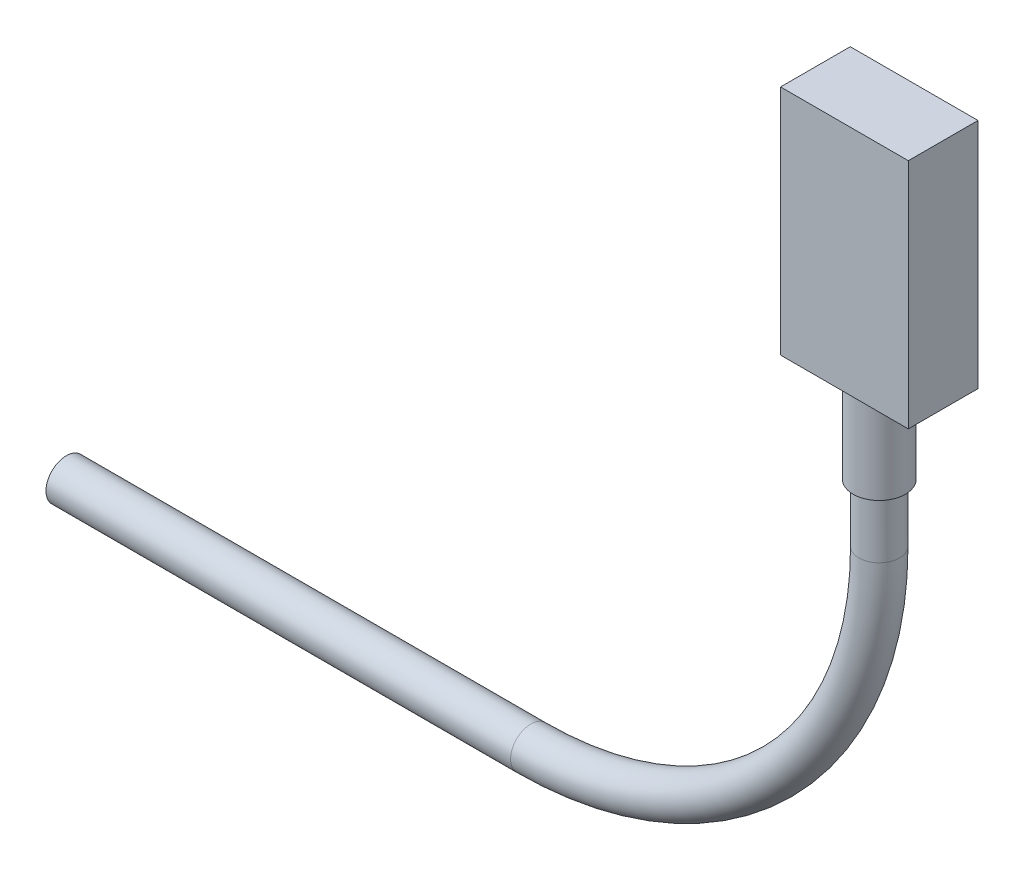
SolidWorks part; units mm, degrees
ref_plane "Front Plane" through (0, 0, 0) normal (0, 0, 1) x (1, 0, 0)
ref_plane "Top Plane" through (0, 0, 0) normal (0, 1, 0) x (1, 0, 0)
ref_plane "Right Plane" through (0, 0, 0) normal (1, 0, 0) x (0, 0, -1)
sketch "Sketch1" plane through (0, 0, 0) normal (0, 1, 0) x (1, 0, 0)
  line L1 (-5.5, 3) -> (5.5, 3)
  line L2 (-5.5, 3) -> (-5.5, -3)
  line L3 (-5.5, -3) -> (5.5, -3)
  line L4 (5.5, 3) -> (5.5, -3)
extrude "Overmould" add sketch "Sketch1" against normal blind 20
ref_plane "Plane_ym20" through (0, -20, 0) normal (0, 1, 0) x (1, 0, 0)
sketch "Sketch2" plane through (0, -20, 0) normal (0, 1, 0) x (1, 0, 0)
  circle A0 centre (0, 0) radius 2.25
extrude "Strain_relief" add sketch "Sketch2" against normal blind 8
sketch "Sketch3" plane through (0, 0, 0) normal (0, 0, 1) x (1, 0, 0)
  line L0 (0, -28) -> (0, -33)
  line L1 (-30, -63) -> (-70, -63)
  arc A0 (0, -33) -> (-30, -63) centre (-30, -33) cw
sweep "Lead" add path "Sketch3" circular profile diameter 3.5 parameters "D3"=3.5
